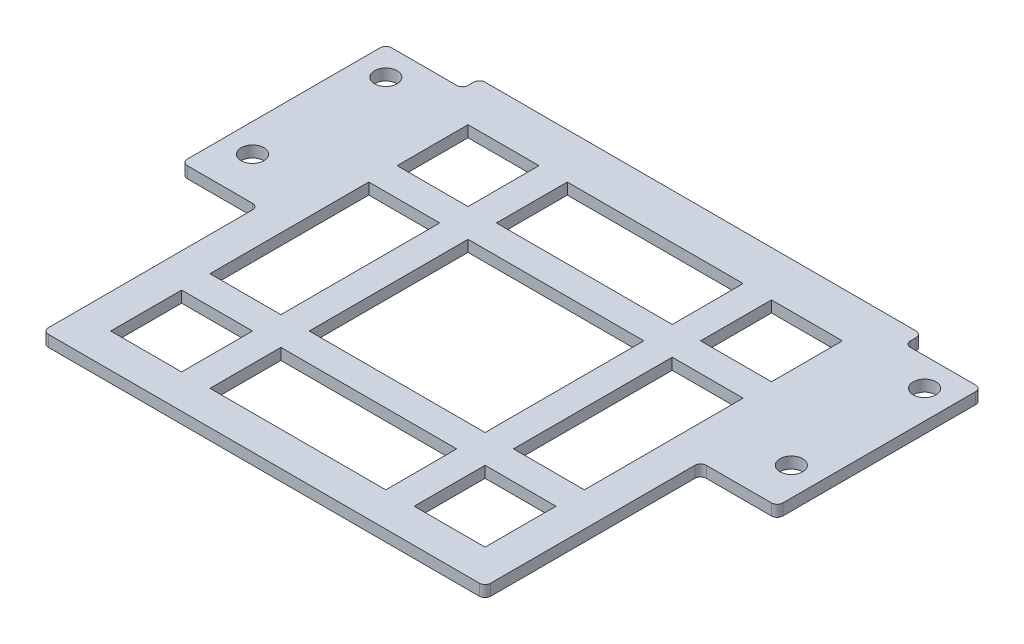
SolidWorks part; units mm, degrees
material "Thornel Mat VMA"
ref_plane "前视基准面" through (0, 0, 0) normal (0, 0, 1) x (1, 0, 0)
ref_plane "上视基准面" through (0, 0, 0) normal (0, 1, 0) x (1, 0, 0)
ref_plane "右视基准面" through (0, 0, 0) normal (1, 0, 0) x (0, 0, -1)
sketch "草图1" plane through (0, 0, 0) normal (0, 1, 0) x (1, 0, 0)
  line L0 (-52.5, -39) -> (-52.5, -3)
  line L1 (-52.5, -3) -> (-39, -3)
  line L2 (-39, -3) -> (-39, 0)
  line L4 (-39, 0) -> (39, 0)
  line L5 (-52.5, -39) -> (-39, -39)
  line L6 (-39, -39) -> (-39, -77)
  line L7 (-39, -77) -> (39, -77)
  line L8 (-47.5, -31.5) -> (-47.5, -8) construction
  line L9 (0, -1.1) -> (0, 1.1) construction
  line L10 (39, -39) -> (39, -77)
  line L11 (52.5, -39) -> (39, -39)
  line L13 (39, -3) -> (39, 0)
  line L14 (52.5, -3) -> (39, -3)
  line L15 (52.5, -39) -> (52.5, -3)
  circle A0 centre (-47.5, -8) radius 2
  circle A1 centre (-47.5, -31.5) radius 2
  circle A2 centre (47.5, -31.5) radius 2
  circle A3 centre (47.5, -8) radius 2
  dimension "D1" = 4
  dimension "D2" = 8.5
  dimension "D3" = 5
  dimension "D4" = 23.5
  dimension "D7" = 95
  dimension "D5" = 7.5
  dimension "D6" = 77
  dimension "D8" = 3
  dimension "D9" = 5
extrude "凸台-拉伸1" add sketch "草图1" along normal blind 2
sketch "草图3" plane through (0, 2, 0) normal (0, 1, 0) x (1, 0, 0)
  line L5 (39, -8) -> (-39, -8)
  line L6 (-33, -39) -> (-33, -71)
  line L7 (33, -71) -> (33, -39)
  line L8 (-33, -71) -> (33, -71)
  line L9 (-33, -8) -> (-33, -71)
  line L10 (33, -71) -> (33, -8)
  line L11 (-33, -71) -> (33, -71)
  line L12 (33, -8) -> (-33, -8)
  point P0 (33.7488, -8)
  dimension "D1" = 6
  dimension "D2" = 8
extrude "切除-拉伸1" cut sketch "草图3" against normal through all
fillet "圆角1" radius 1 12 edges at (-52.5, 1, 3) (-39, 1, 3) (-39, 1, 0) (39, 1, 0) (39, 1, 3) (52.5, 1, 3) (52.5, 1, 39) (39, 1, 39) (39, 1, 77) (-39, 1, 77) (-39, 1, 39) (-52.5, 1, 39)
sketch "草图4" plane through (0, 2, 0) normal (0, 1, 0) x (1, 0, 0)
  line L0 (-33, -23) -> (33, -23)
  line L1 (-33, -8) -> (-33, -71) construction
  line L2 (33, -71) -> (33, -8) construction
  line L3 (-33, -56) -> (33, -56)
  line L4 (-18, -71) -> (-18, -8)
  line L5 (-33, -71) -> (33, -71) construction
  line L6 (33, -8) -> (-33, -8) construction
  line L7 (18, -8) -> (18, -71)
  point P16 (-30.3298, -8)
  point P17 (-26.9108, -8)
  dimension "D1" = 33
  dimension "D2" = 36
  dimension "D3" = 15
  dimension "D4" = 15
extrude "拉伸-薄壁1" add sketch "草图4" against normal up to surface (2 mm away) thin up to face at (0, 0, 39.5) thin type mid plane wall 5
